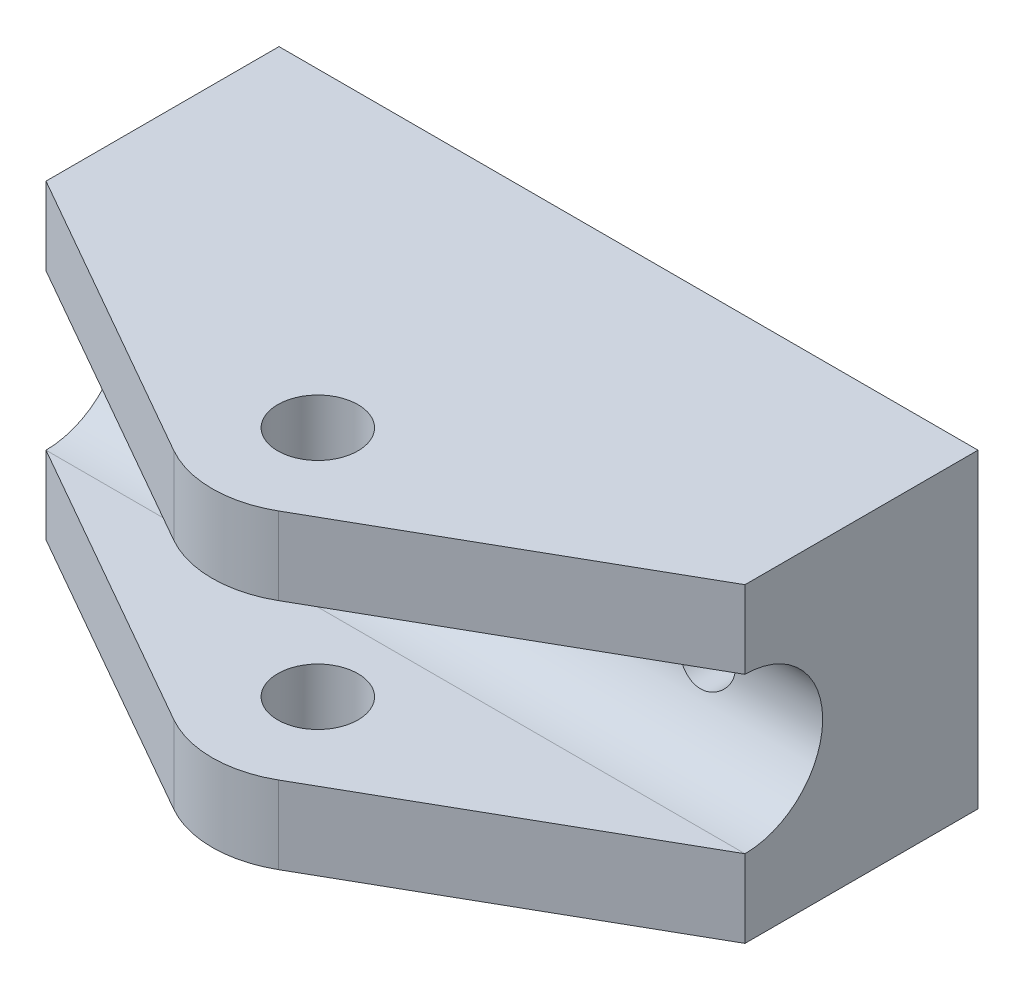
SolidWorks part; units mm, degrees
ref_plane "Front Plane" through (0, 0, 0) normal (0, 0, 1) x (1, 0, 0)
ref_plane "Top Plane" through (0, 0, 0) normal (0, 1, 0) x (1, 0, 0)
ref_plane "Right Plane" through (0, 0, 0) normal (1, 0, 0) x (0, 0, -1)
sketch "Sketch1" plane through (0, 0, 0) normal (0, 0, 1) x (1, 0, 0)
  line L1 (254.9308, 254) -> (197.7808, 254)
  line L2 (254.9308, 254) -> (254.9308, 228.6)
  line L3 (254.9308, 228.6) -> (197.7808, 228.6)
  line L4 (197.7808, 254) -> (197.7808, 228.6)
  line L5 (254.9308, 254) -> (197.7808, 228.6) construction
  line L6 (254.9308, 228.6) -> (197.7808, 254) construction
  line L11 (264.4558, 254) -> (-34.0111, 254) construction
  line L12 (264.4558, 228.6) -> (-34.0111, 228.6) construction
  line L13 (207.3058, 241.3) -> (245.4058, 241.3)
  circle A0 centre (245.4058, 241.3) radius 2.3813 construction
  circle A1 centre (207.3058, 241.3) radius 2.3813 construction
  circle A2 centre (245.4058, 241.3) radius 2.3813
  circle A3 centre (207.3058, 241.3) radius 2.3813
  point P6 (226.3558, 241.3)
  point P11 (0, 0)
  point P12 (226.3558, 241.3)
  point P17 (195.1051, 254)
  dimension "D1" = 57.15
extrude "Boss-Extrude1" add sketch "Sketch1" along normal blind 34.036
sketch "Sketch2" plane through (0, 254, 0) normal (0, 1, 0) x (1, 0, 0)
  line L0 (254.9308, -19.05) -> (230.633, -32.9024)
  line L1 (197.7808, -19.05) -> (222.0786, -32.9024)
  line L2 (254.9308, -34.036) -> (226.6818, -42.3141)
  line L3 (226.6818, -42.3141) -> (197.7808, -34.036)
  line L4 (254.9308, 0) -> (197.7808, 0)
  line L5 (197.7808, 0) -> (197.7808, -34.036)
  line L6 (197.7808, -34.036) -> (254.9308, -34.036)
  line L7 (254.9308, -34.036) -> (254.9308, 0)
  line L8 (254.9308, 0) -> (197.7808, 0)
  line L9 (197.7808, 0) -> (197.7808, -34.036)
  line L10 (197.7808, -34.036) -> (254.9308, -34.036) construction
  line L11 (254.9308, -34.036) -> (254.9308, 0)
  arc A0 (230.633, -32.9024) -> (222.0786, -32.9024) centre (226.3558, -25.4) cw
  circle A1 centre (226.3558, -25.4) radius 3.2814
  point P12 (0, 0)
  point P13 (208.9408, -28.268)
  point P14 (244.204, -28.3329)
  point P15 (232.1723, -32.4508)
  point P16 (0, 0)
  line M8 (197.7808, 0) -> (197.7808, -34.036)
  line M9 (197.7808, -34.036) -> (254.9308, -34.036)
  line M10 (254.9308, -34.036) -> (254.9308, 0)
  dimension "D2" = 19.05
  dimension "D3" = 25.4
  dimension "D1" = 0
extrude "Cut-Extrude1" cut sketch "Sketch2" against normal through all contours L0 A0 M9 M10 | A0 L1 M9 M8 | L3 L2 M9 | A1
sketch "Sketch3" plane through (197.7808, 0, 0) normal (-1, 0, 0) x (0, 0, 1)
  line L0 (19.05, 241.3) -> (49.022, 241.3) construction
  line L1 (19.05, 247.65) -> (49.022, 247.65)
  line L2 (19.05, 234.95) -> (49.022, 234.95)
  line L3 (34.036, 228.6) -> (34.036, 254) construction
  line L4 (19.05, 228.6) -> (19.05, 254) construction
  arc A0 (19.05, 247.65) -> (19.05, 234.95) centre (19.05, 241.3) ccw
  arc A1 (49.022, 234.95) -> (49.022, 247.65) centre (49.022, 241.3) ccw
  point P2 (34.036, 241.3)
  point P7 (0, 0)
  point P10 (19.05, 241.3)
  dimension "D1" = 6.35
extrude "Cut-Extrude2" cut sketch "Sketch3" against normal through all
